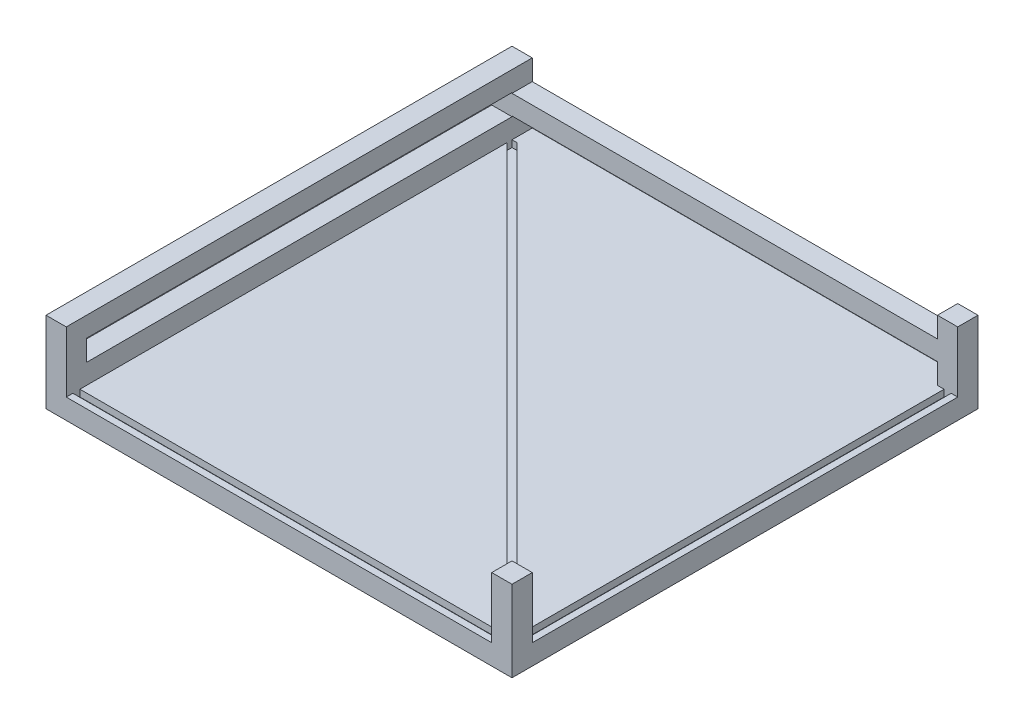
SolidWorks part; units mm, degrees
ref_plane "Front Plane" through (0, 0, 0) normal (0, 0, 1) x (1, 0, 0)
ref_plane "Top Plane" through (0, 0, 0) normal (0, 1, 0) x (1, 0, 0)
ref_plane "Right Plane" through (0, 0, 0) normal (1, 0, 0) x (0, 0, -1)
sketch "Sketch1" plane through (0, 0, 0) normal (0, 1, 0) x (1, 0, 0)
  line L0 (-57.5, 57.5) -> (57.5, -57.5) construction
  line L1 (-57.5, 57.5) -> (57.5, 57.5)
  line L2 (-57.5, 57.5) -> (-57.5, -57.5)
  line L3 (-57.5, -57.5) -> (57.5, -57.5)
  line L4 (57.5, 57.5) -> (57.5, -57.5)
  line L5 (57.5, 57.5) -> (-57.5, -57.5) construction
  point P4 (0, 0)
  dimension "D1" = 115
  dimension "D2" = 115
extrude "Base" add sketch "Sketch1" along normal blind 5
sketch "Sketch2" plane through (-57.5, 0, 0) normal (-1, 0, 0) x (0, 0, 1)
  line L0 (-52.5, 15.08) -> (-52.5, 20) construction
  line L1 (-57.5, 5) -> (57.5, 5)
  line L2 (-57.5, 5) -> (-57.5, 20)
  line L3 (-57.5, 20) -> (57.5, 20)
  line L4 (57.5, 5) -> (57.5, 20)
  line L5 (-52.5, 9.92) -> (52.5, 9.92)
  line L6 (-52.5, 9.92) -> (-52.5, 15.08)
  line L7 (-52.5, 15.08) -> (52.5, 15.08)
  line L8 (52.5, 9.92) -> (52.5, 15.08)
  line L9 (-52.5, 15.08) -> (-57.5, 15.08) construction
  line L10 (-52.5, 9.92) -> (-52.5, 5) construction
  line L11 (-52.5, 9.92) -> (-57.5, 9.92) construction
  line L12 (52.5, 15.08) -> (52.5, 20) construction
  line L13 (52.5, 15.08) -> (57.5, 15.08) construction
  line L14 (52.5, 9.92) -> (57.5, 9.92) construction
  line L15 (52.5, 9.92) -> (52.5, 5) construction
  line M15 (57.5, 5) -> (-57.5, 5)
  dimension "D1" = 4.92
  dimension "D2" = 4.92
  dimension "D3" = 5
  dimension "D4" = 5
  dimension "D5" = 15
sketch "Sketch4" plane through (0, 0, -57.5) normal (0, 0, -1) x (-1, 0, 0)
  line L0 (57.5, 5) -> (57.5, 20) construction
  line L1 (-57.5, 5) -> (-52.5, 5)
  line L2 (-57.5, 5) -> (-57.5, 20)
  line L3 (-57.5, 20) -> (-52.5, 20)
  line L4 (57.5, 5) -> (57.5, 20)
  line L5 (57.5, 15.08) -> (57.5, 20) construction
  line L6 (52.5, 14.92) -> (52.5, 20)
  line L7 (-52.5, 14.92) -> (52.5, 14.92)
  line L9 (-52.5, 10.08) -> (52.5, 10.08)
  line L11 (52.5, 14.92) -> (57.5, 14.92) construction
  line L12 (52.5, 10.08) -> (57.5, 10.08) construction
  line L13 (52.5, 10.08) -> (52.5, 5)
  line L14 (-52.5, 14.92) -> (-52.5, 20)
  line L15 (-52.5, 14.92) -> (-57.5, 14.92) construction
  line L16 (-52.5, 10.08) -> (-57.5, 10.08) construction
  line L17 (-52.5, 10.08) -> (-52.5, 5)
  line L18 (52.5, 20) -> (57.5, 20)
  line L19 (52.5, 5) -> (57.5, 5)
  dimension "D1" = 5.08
  dimension "D3" = 5.08
  dimension "D5" = 5
  dimension "D2" = 5
  dimension "D6" = 5
  dimension "D7" = 5
  dimension "D4" = 15
extrude "Frame1" add sketch "Sketch2" against normal up to vertex (5 mm away) contours L4 L3 L2 L8 L5 L6 L7 M15
extrude "Frame2" add sketch "Sketch4" against normal up to vertex contours L2 L3 L14 L7 L6 L18 L4 L19 L13 L9 L17 L1
sketch "Sketch5" plane through (0, 5, 0) normal (0, 1, 0) x (1, 0, 0)
  line L1 (57.5, -57.5) -> (52.5, -57.5)
  line L2 (57.5, -57.5) -> (57.5, -52.5)
  line L3 (57.5, -52.5) -> (52.5, -52.5)
  line L4 (52.5, -57.5) -> (52.5, -52.5)
  dimension "D1" = 5
  dimension "D2" = 5
extrude "Post" add sketch "Sketch5" along normal up to surface (15 mm away) contours L3 L4 L1 L2 up to face at (-55, 20, 0)
sketch "Sketch6" plane through (0, 5, 0) normal (0, 1, 0) x (1, 0, 0)
  line L0 (57.5, 52.5) -> (52.5, 52.5) construction
  line L1 (54.1267, 52.5) -> (55.8733, 52.5)
  line L2 (54.1267, 52.5) -> (54.1267, -52.5)
  line L3 (54.1267, -52.5) -> (55.8733, -52.5)
  line L4 (55.8733, 52.5) -> (55.8733, -52.5)
  line L5 (52.5, -52.5) -> (57.5, -52.5) construction
  line L6 (52.5, -57.5) -> (52.5, -52.5) construction
  line L7 (52.5, -54.1267) -> (-52.5, -54.1267)
  line L8 (52.5, -54.1267) -> (52.5, -55.8733)
  line L9 (52.5, -55.8733) -> (-52.5, -55.8733)
  line L10 (-52.5, -54.1267) -> (-52.5, -55.8733)
  line L11 (-52.5, 57.5) -> (-52.5, -57.5) construction
  line L12 (52.5, -52.5) -> (52.5, -57.5) construction
  line L13 (57.5, -52.5) -> (57.5, 52.5) construction
  line L14 (-52.5, -57.5) -> (52.5, -57.5) construction
  dimension "D1" = 1.6267
  dimension "D2" = 1.6267
  dimension "D3" = 1.6267
  dimension "D4" = 1.6267
extrude "Tracks" cut sketch "Sketch6" against normal blind 1.6667
sketch "Sketch7" plane through (0, 5, 0) normal (0, 1, 0) x (1, 0, 0)
  line L0 (53.7351, -52.5) -> (-51.2649, 52.5)
  line L1 (52.5, -52.5) -> (57.5, -52.5) construction
  line L2 (52.5, 52.5) -> (-52.5, 52.5) construction
  line L4 (-52.5, 57.5) -> (-52.5, -57.5) construction
  line L5 (-52.5, 51.2649) -> (52.5, -53.7351)
  line L6 (52.5, -52.5) -> (52.5, -57.5) construction
  line L7 (52.5, -53.7351) -> (52.5, -52.5)
  line L8 (52.5, -54.1267) -> (52.5, -52.5) construction
  line L9 (52.5, -52.5) -> (53.7351, -52.5)
  line L10 (-52.5, 51.2649) -> (-52.5, 52.5)
  line L11 (-52.5, 52.5) -> (-51.2649, 52.5)
  point P6 (53.0985, -52.5)
  point P18 (0, 0)
  dimension "D1" = 1.7467
extrude "Cut-Extrude1" cut sketch "Sketch7" against normal blind 1.67
equation "\"Frame side length\"= \"Useful Tray Size\" + \"Universal Bar Height\" * 3"
equation "\"D1@Sketch1\"=\"Frame side length\""
equation "\"D2@Sketch1\"=\"Frame side length\""
equation "\"Universal Bar Height\"= 5mm"
equation "\"D1@Base\" = \"Universal Bar Height\""
equation "\"D2@Sketch2\"=\"Universal Bar Height\"-\"Frame Tolerance\"/2"
equation "\"D3@Sketch2\"=\"Universal Bar Height\""
equation "\"D4@Sketch2\"=\"Universal Bar Height\""
equation "\"D5@Sketch4\"=\"Universal Bar Height\""
equation "\"D2@Sketch4\"=\"Universal Bar Height\""
equation "\"D6@Sketch4\"=\"Universal Bar Height\""
equation "\"D7@Sketch4\"=\"Universal Bar Height\""
equation "\"D1@Sketch5\"=\"Universal Bar Height\""
equation "\"D2@Sketch5\"=\"Universal Bar Height\""
equation "\"D1@Sketch6\"=\"Universal Bar Height\"/3 - \"Track Tolerance\"/2"
equation "\"D2@Sketch6\"=\"Universal Bar Height\"/3 - \"Track Tolerance\"/2"
equation "\"D3@Sketch6\"=\"Universal Bar Height\"/3 - \"Track Tolerance\"/2"
equation "\"D4@Sketch6\"=\"Universal Bar Height\"/3 - \"Track Tolerance\"/2"
equation "\"D1@Tracks\" = \"Universal Bar Height\" / 3"
equation "\"Useful Tray Size\"= 100mm"
equation "\"Frame Tolerance\" = 0.16mm"
equation "\"D1@Sketch2\"=\"Universal Bar Height\"-\"Frame Tolerance\"/2"
equation "\"D5@Sketch2\"=\"Universal Bar Height\"*3"
equation "\"D1@Sketch4\"=\"Universal Bar Height\"+\"Frame Tolerance\"/2"
equation "\"D3@Sketch4\"=\"Universal Bar Height\"+\"Frame Tolerance\"/2"
equation "\"Track Tolerance\"= 0.08mm"
equation "\"D1@Sketch7\"=\"Universal Bar Height\"/3 + \"Track Tolerance\""
